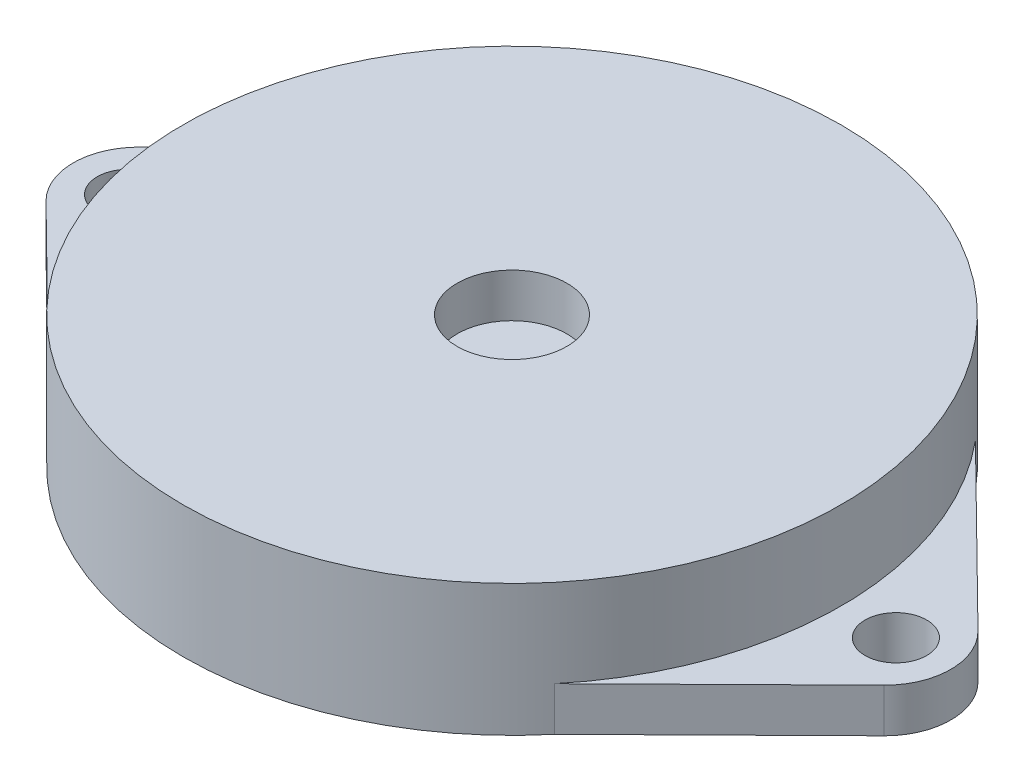
SolidWorks part; units mm, degrees
ref_plane "前视基准面" through (0, 0, 0) normal (0, 0, 1) x (1, 0, 0)
ref_plane "上视基准面" through (0, 0, 0) normal (0, 1, 0) x (1, 0, 0)
ref_plane "右视基准面" through (0, 0, 0) normal (1, 0, 0) x (0, 0, -1)
sketch "草图1" plane through (0, 0, 0) normal (0, 1, 0) x (1, 0, 0)
  circle A0 centre (0, 0) radius 15
  dimension "D1" = 30
extrude "凸台-拉伸1" add sketch "草图1" along normal blind 6
sketch "草图2" plane through (0, 6, 0) normal (0, 1, 0) x (1, 0, 0)
  circle A0 centre (0, 0) radius 2.5
  dimension "D1" = 5
extrude "切除-拉伸1" cut sketch "草图2" against normal blind 2
sketch "草图3" plane through (0, 0, 0) normal (0, -1, 0) x (1, 0, 0)
  line L0 (3.23, 0) -> (-25.076, 0) construction
  line L1 (0, 15.805) -> (0, -16.7913) construction
  line L2 (-9.4172, 11.6755) -> (-19.1047, 2.1378)
  line L3 (-9.4172, -11.6755) -> (-19.1047, -2.1378)
  line L4 (-9.4172, 11.6755) -> (-9.4172, -11.6755)
  line L5 (9.4172, 11.6755) -> (9.4172, -11.6755)
  line L6 (9.4172, -11.6755) -> (19.1047, -2.1378)
  line L7 (9.4172, 11.6755) -> (19.1047, 2.1378)
  circle A0 centre (-17.5, 0) radius 1.4054
  circle A1 centre (0, 0) radius 15 construction
  arc A2 (-19.1047, -2.1378) -> (-19.1047, 2.1378) centre (-17, 0) cw
  arc A3 (19.1047, -2.1378) -> (19.1047, 2.1378) centre (17, 0) ccw
  circle A4 centre (17.5, 0) radius 1.4054
  point P14 (-21.2761, 0)
  dimension "D1" = 3
  dimension "D3" = 34
  dimension "D2" = 35
extrude "凸台-拉伸2" add sketch "草图3" against normal blind 2
